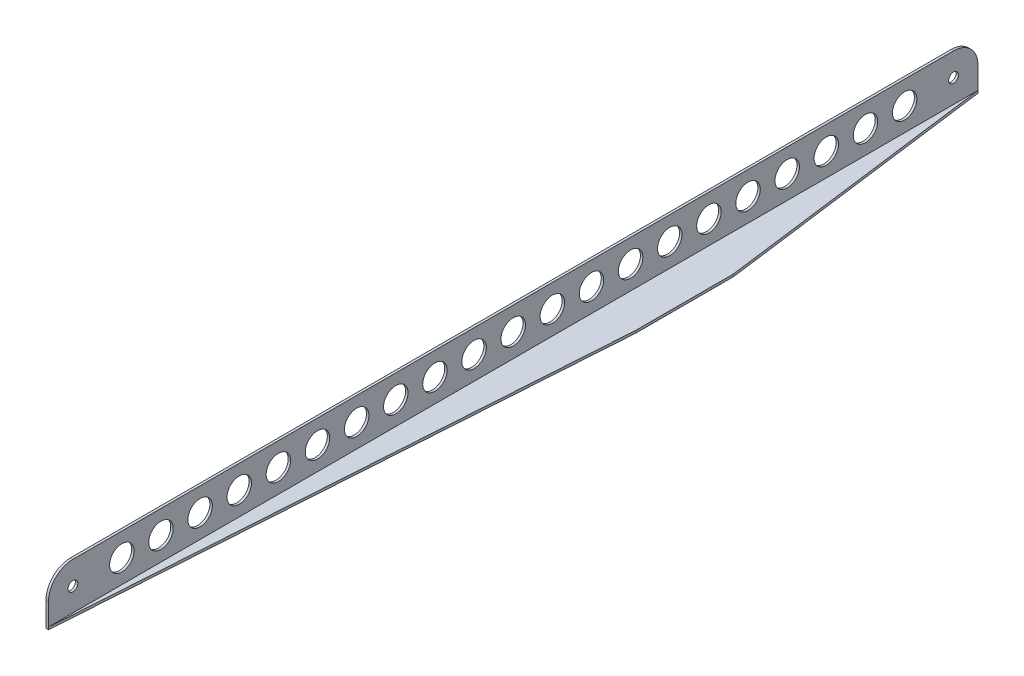
SolidWorks part; units mm, degrees
ref_plane "Front" through (0, 0, 0) normal (0, 0, 1) x (1, 0, 0)
ref_plane "Top" through (0, 0, 0) normal (0, 1, 0) x (1, 0, 0)
ref_plane "Right" through (0, 0, 0) normal (1, 0, 0) x (0, 0, -1)
sketch "Sketch1" plane through (0, 0, 0) normal (0, 0, 1) x (1, 0, 0)
  line L0 (0, -15.388) -> (0, -35.388)
  line L1 (0, -35.388) -> (20, -35.388)
  line L2 (20, -35.388) -> (20, -34.388)
  line L3 (20, -34.388) -> (1, -34.388)
  line L4 (1, -34.388) -> (1, -15.388)
  line L5 (1, -15.388) -> (0, -15.388)
  point P7 (0, -15.6983)
  dimension "D1" = 20
  dimension "D2" = 20
  dimension "D3" = 1
  dimension "D4" = 1
extrude "Boss-Extrude1" add sketch "Sketch1" along normal blind 380
sketch "Sketch2" plane through (1, 0, 0) normal (1, 0, 0) x (0, 0, -1)
  line L0 (0, -34.388) -> (0, -15.388) construction
  line L1 (-380, -34.388) -> (-380, -15.388) construction
  circle A0 centre (-10, -24.888) radius 2
  circle A1 centre (-370, -24.888) radius 2
  point P8 (0, 0)
  point P9 (-380, -24.888)
  point P10 (0, -24.888)
  dimension "D1" = 10
  dimension "D3" = 4
  dimension "D2" = 10
extrude "Cut-Extrude1" cut sketch "Sketch2" against normal blind 10
sketch "Sketch4" plane through (0, -34.388, 0) normal (0, 1, 0) x (1, 0, 0)
  line L0 (1, 0) -> (16, -115)
  line L2 (16, -115) -> (16, -155)
  line L3 (16, -155) -> (1, -380)
  line L4 (1, -380) -> (1, -389.2125)
  line L5 (1, -389.2125) -> (24.9093, -389.2125)
  line L6 (24.9093, -389.2125) -> (24.9093, 2.4023)
  line L7 (24.9093, 2.4023) -> (1, 2.4023)
  line L8 (1, 2.4023) -> (1, 0)
  line L9 (20, 0) -> (1, 0) construction
  line L11 (1, -380) -> (1, 0) construction
  point P14 (0, 0)
  point P15 (0, 0)
  dimension "D1" = 115
  dimension "D2" = 40
  dimension "D3" = 15
extrude "Cut-Extrude2" cut sketch "Sketch4" against normal blind 10
sketch "Sketch5" plane through (1, 0, 0) normal (1, 0, 0) x (0, 0, -1)
  line L0 (-380, -34.388) -> (-380, -15.388) construction
  circle A0 centre (-350, -24.888) radius 5
  point P2 (0, 0)
  point P5 (-380, -24.888)
  dimension "D1" = 10
  dimension "D2" = 30
extrude "Cut-Extrude3" cut sketch "Sketch5" against normal blind 10 contours A0
pattern_linear "LPattern1" count 21 spacing 16 along (0, 0, -1) of "Cut-Extrude3"
fillet "Fillet1" radius 10 2 edges at (0.5, -15.388, 0) (0.5, -15.388, 380)
